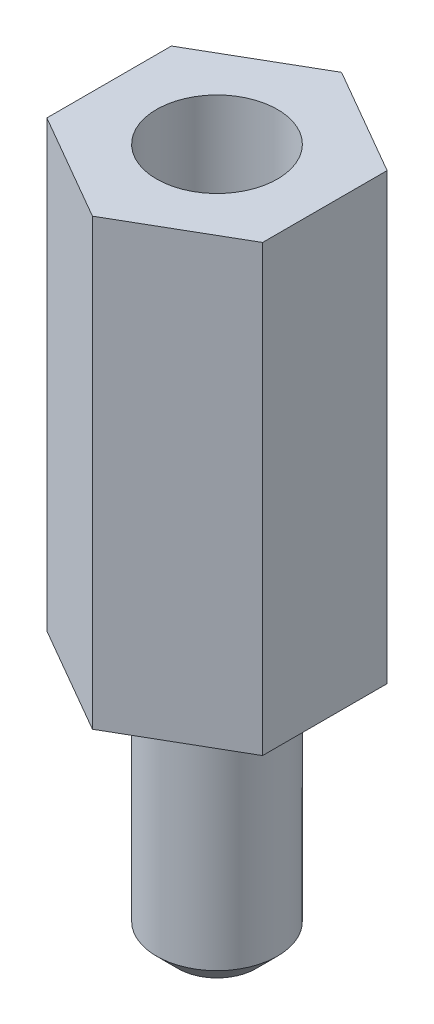
SolidWorks part; units mm, degrees
ref_plane "Спереди" through (0, 0, 0) normal (0, 0, 1) x (1, 0, 0)
ref_plane "Сверху" through (0, 0, 0) normal (0, 1, 0) x (1, 0, 0)
ref_plane "Справа" through (0, 0, 0) normal (1, 0, 0) x (0, 0, -1)
sketch "Эскиз1" plane through (0, 0, 0) normal (0, 1, 0) x (1, 0, 0)
  line L1 (0, 2.8868) -> (-2.5, 1.4434)
  line L2 (-2.5, 1.4434) -> (-2.5, -1.4434)
  line L3 (-2.5, -1.4434) -> (0, -2.8868)
  line L4 (0, -2.8868) -> (2.5, -1.4434)
  line L5 (2.5, -1.4434) -> (2.5, 1.4434)
  line L6 (2.5, 1.4434) -> (0, 2.8868)
  circle A0 centre (0, 0) radius 2.5 construction
  dimension "D1" = 5
extrude "Бобышка-Вытянуть1" add sketch "Эскиз1" along normal blind 10.3 contours L1 L2 L3 L4 L5 L6
sketch "Эскиз2" plane through (0, 0, 0) normal (0, -1, 0) x (1, 0, 0)
  circle A0 centre (0, 0) radius 1.4
  dimension "D1" = 2.8
extrude "Бобышка-Вытянуть2" add sketch "Эскиз2" along normal blind 5.8
chamfer "Фаска1" distance 0.5 angle 45 1 edges at (0, -5.8, -1.4)
sketch "Эскиз3" plane through (0, 10.3, 0) normal (0, 1, 0) x (1, 0, 0)
  circle A0 centre (0, 0) radius 1.4
  dimension "D1" = 2.8
extrude "Вырез-Вытянуть1" cut sketch "Эскиз3" against normal blind 7
